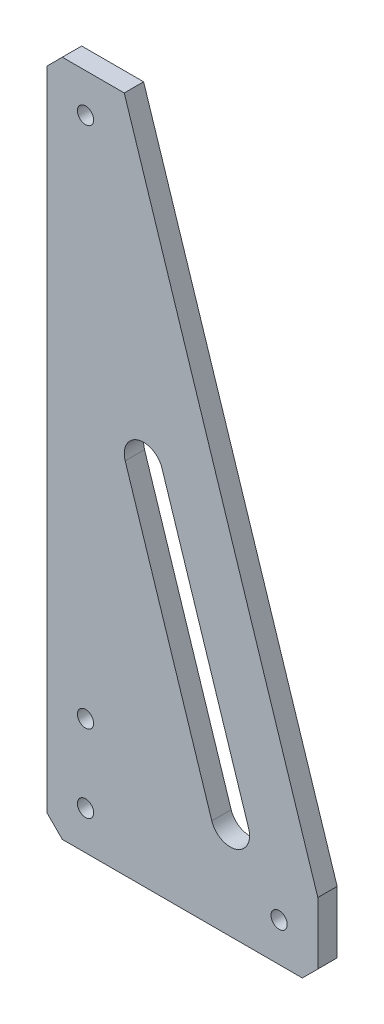
SolidWorks part; units mm, degrees
ref_plane "前视基准面" through (0, 0, 0) normal (0, 0, 1) x (1, 0, 0)
ref_plane "上视基准面" through (0, 0, 0) normal (0, 1, 0) x (1, 0, 0)
ref_plane "右视基准面" through (0, 0, 0) normal (1, 0, 0) x (0, 0, -1)
sketch "草图1" plane through (0, 0, 0) normal (0, 0, 1) x (1, 0, 0)
  line L0 (-35, 87.5) -> (-35, -87.5)
  line L1 (-35, -87.5) -> (35, -87.5)
  line L2 (35, -87.5) -> (35, -67.5)
  line L3 (35, -67.5) -> (-15, 87.5)
  line L4 (-15, 87.5) -> (-35, 87.5)
  line L5 (25, -77.5) -> (-25, -77.5) construction
  line L6 (-25, -77.5) -> (-25, -57.5) construction
  line L7 (-25, -57.5) -> (-25, 77.5) construction
  circle A0 centre (-25, -77.5) radius 2.1
  circle A1 centre (25, -77.5) radius 2.1
  circle A2 centre (-25, 77.5) radius 2.1
  circle A3 centre (-25, -57.5) radius 2.1
  point P0 (-35, 0)
  point P7 (0, -87.5)
  dimension "D3" = 10
  dimension "D6" = 10
  dimension "D7" = 4.2
  dimension "D1" = 20
  dimension "D2" = 20
  dimension "D4" = 10
  dimension "D5" = 10
  dimension "D8" = 175
  dimension "D9" = 70
  dimension "D10" = 20
extrude "凸台-拉伸1" add sketch "草图1" along normal mid plane 5
chamfer "倒角1" distance 4 angle 45 3 edges at (35, -87.5, 0) (-35, -87.5, 0) (-35, 87.5, 0)
chamfer "倒角2" distance 2 angle 45 4 edges at (27.1, -77.5, -2.5) (-22.9, -77.5, -2.5) (-22.9, -57.5, -2.5) (-22.9, 77.5, -2.5)
sketch "草图2" plane through (0, 0, -2.5) normal (0, 0, -1) x (-1, 0, 0)
  line L0 (-12.3723, -62.5) -> (10, 6.854) construction
  line L1 (-17.1308, -60.965) -> (5.2415, 8.389)
  line L2 (-7.6137, -64.035) -> (14.7585, 5.319)
  line L3 (-35, -67.5) -> (15, 87.5) construction
  line L4 (35, 83.5) -> (35, -83.5) construction
  arc A0 (-17.1308, -60.965) -> (-7.6137, -64.035) centre (-12.3723, -62.5) ccw
  arc A1 (14.7585, 5.319) -> (5.2415, 8.389) centre (10, 6.854) ccw
  circle A2 centre (-25, -77.5) radius 2.1 construction
  point P2 (-1.1861, -27.823)
  dimension "D2" = 5
  dimension "D1" = 15
  dimension "D3" = 15
  dimension "D4" = 25
extrude "切除-拉伸1" cut sketch "草图2" against normal through all
